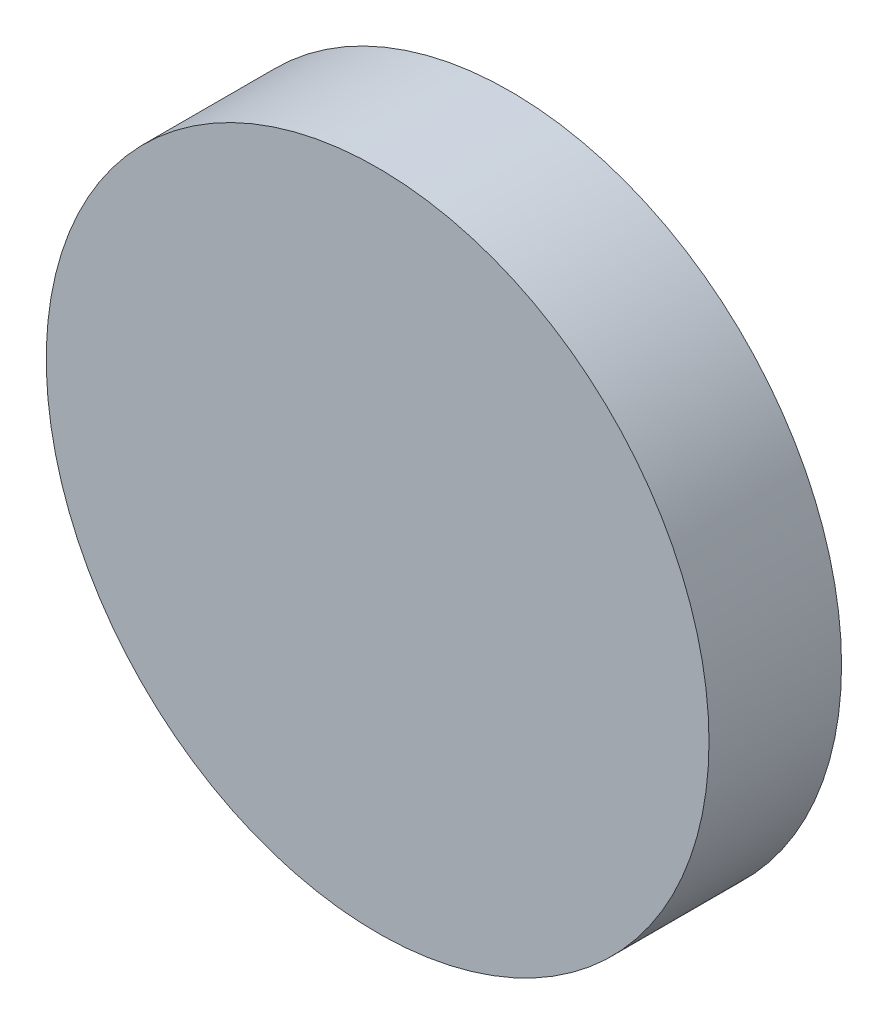
SolidWorks part; units mm, degrees
material "Glass"
ref_plane "Front Plane" through (0, 0, 0) normal (0, 0, 1) x (1, 0, 0)
ref_plane "Top Plane" through (0, 0, 0) normal (0, 1, 0) x (1, 0, 0)
ref_plane "Right Plane" through (0, 0, 0) normal (1, 0, 0) x (0, 0, -1)
sketch "Sketch1" plane through (0, 0, 0) normal (0, 0, 1) x (1, 0, 0)
  circle A0 centre (0, 0) radius 6.35
  dimension "D1" = 12.7
extrude "Boss-Extrude1" add sketch "Sketch1" along normal blind 2.54
